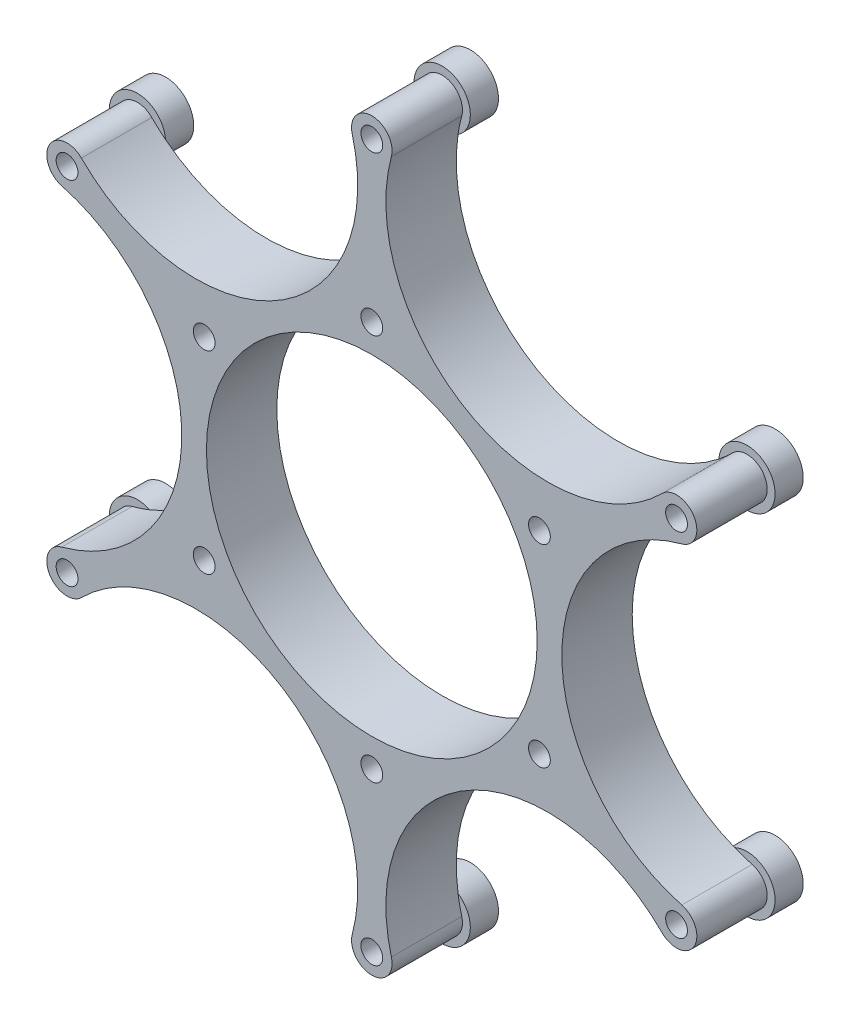
SolidWorks part; units mm, degrees
material "A-玻璃纤维"
ref_plane "前视基准面" through (0, 0, 0) normal (0, 0, 1) x (1, 0, 0)
ref_plane "上视基准面" through (0, 0, 0) normal (0, 1, 0) x (1, 0, 0)
ref_plane "右视基准面" through (0, 0, 0) normal (1, 0, 0) x (0, 0, -1)
sketch "草图1" plane through (0, 0, 0) normal (0, 0, 1) x (1, 0, 0)
  line L0 (0, 0) -> (0, 50) construction
  line L1 (0, 0) -> (43.3013, 25) construction
  line L2 (-43.3013, 25) -> (0, 0) construction
  line L3 (0, 0) -> (-25, 43.3013) construction
  line L4 (-25, 43.3013) -> (-66.3459, 35.9177) construction
  line L5 (-43.3013, 25) -> (-45.7971, 26.441) construction
  line L6 (0, 52.8819) -> (0, 50) construction
  line L7 (0, 0) -> (-2.7837, 49.2541) construction
  line L8 (0, 0) -> (41.2635, 27.0378) construction
  circle A0 centre (0, 0) radius 23.5
  circle A1 centre (0, 0) radius 73 construction
  circle A2 centre (0, 0) radius 50 construction
  circle A3 centre (0, 50) radius 4 construction
  circle A4 centre (43.3013, 25) radius 4 construction
  circle A5 centre (43.3013, -25) radius 4 construction
  circle A6 centre (0, -50) radius 4 construction
  circle A7 centre (-43.3013, -25) radius 4 construction
  circle A8 centre (-43.3013, 25) radius 4 construction
  circle A9 centre (-25, 43.3013) radius 21 construction
  circle A10 centre (-66.3459, 35.9177) radius 21 construction
  arc A13 (0, 52.8819) -> (-2.7837, 49.2541) centre (0, 50) ccw
  arc A14 (-41.2635, 27.0378) -> (-45.7971, 26.441) centre (-43.3013, 25) ccw
  arc A15 (-41.2635, 27.0378) -> (-2.7837, 49.2541) centre (-25, 43.3013) ccw
  arc A16 (2.7837, 49.2541) -> (41.2635, 27.0378) centre (25, 43.3013) ccw
  arc A17 (45.7971, 26.441) -> (41.2635, 27.0378) centre (43.3013, 25) ccw
  arc A18 (2.7837, 49.2541) -> (0, 52.8819) centre (0, 50) ccw
  arc A19 (44.0472, 22.2163) -> (44.0472, -22.2163) centre (50, 0) ccw
  arc A20 (45.7971, -26.441) -> (44.0472, -22.2163) centre (43.3013, -25) ccw
  arc A21 (44.0472, 22.2163) -> (45.7971, 26.441) centre (43.3013, 25) ccw
  arc A22 (41.2635, -27.0378) -> (2.7837, -49.2541) centre (25, -43.3013) ccw
  arc A23 (0, -52.8819) -> (2.7837, -49.2541) centre (0, -50) ccw
  arc A24 (41.2635, -27.0378) -> (45.7971, -26.441) centre (43.3013, -25) ccw
  arc A25 (-2.7837, -49.2541) -> (-41.2635, -27.0378) centre (-25, -43.3013) ccw
  arc A26 (-45.7971, -26.441) -> (-41.2635, -27.0378) centre (-43.3013, -25) ccw
  arc A27 (-2.7837, -49.2541) -> (0, -52.8819) centre (0, -50) ccw
  arc A28 (-44.0472, -22.2163) -> (-44.0472, 22.2163) centre (-50, 0) ccw
  arc A29 (-45.7971, 26.441) -> (-44.0472, 22.2163) centre (-43.3013, 25) ccw
  arc A30 (-44.0472, -22.2163) -> (-45.7971, -26.441) centre (-43.3013, -25) ccw
  circle A31 centre (0, 50) radius 4.8819 construction
  circle A32 centre (-43.3013, 25) radius 4.5 construction
  dimension "D1" = 47
  dimension "D2" = 100
  dimension "D3" = 8
  dimension "D7" = 42
  dimension "D8" = 2
  dimension "D9" = 146
  dimension "D10" = 23
  dimension "D13" = 9
  dimension "D5" = 60
  dimension "D6" = 30
  dimension "D11" = 6
  dimension "D12" = 60
  dimension "D4" = 6
extrude "凸台-拉伸1" add sketch "草图1" along normal mid plane 10 contours A28 A30 A26 A25 A27 A23 A22 A24 A20 A19 A21 A17 A16 A18 A13 A15 A14 A29 A0
sketch "草图2" plane through (0, 0, 5) normal (0, 0, 1) x (1, 0, 0)
  circle A0 centre (0, 50) radius 1.55
  dimension "D1" = 3.1
extrude "切除-拉伸1" cut sketch "草图2" against normal blind 10
pattern_circular "阵列(圆周)1" count 6 over 360 about axis through (0, 0, 0) along (0, 0, 1) of "切除-拉伸1"
sketch "草图3" plane through (0, 0, 5) normal (0, 0, 1) x (1, 0, 0)
  line L0 (0, 0) -> (0, 27.5) construction
  line L1 (0, 0) -> (23.8157, 13.75) construction
  circle A1 centre (0, 27.5) radius 1.55
  circle A2 centre (0, 0) radius 27.5
  circle A3 centre (0, 0) radius 27.5 construction
  circle A4 centre (23.8157, 13.75) radius 1.55
  circle A5 centre (23.8157, -13.75) radius 1.55
  circle A6 centre (0, -27.5) radius 1.55
  circle A7 centre (-23.8157, -13.75) radius 1.55
  circle A8 centre (-23.8157, 13.75) radius 1.55
  dimension "D2" = 3.1
  dimension "D4" = 60
  dimension "D1" = 4
  dimension "D3" = 6
extrude "切除-拉伸2" cut sketch "草图3" against normal blind 10
sketch "草图4" plane through (0, 0, -5) normal (0, 0, -1) x (-1, 0, 0)
  circle A0 centre (-43.3013, 25) radius 1.5
  circle A1 centre (-43.3013, 25) radius 4
  dimension "D1" = 3
  dimension "D2" = 8
extrude "凸台-拉伸2" add sketch "草图4" along normal blind 4
pattern_circular "阵列(圆周)2" count 6 over 360 about axis through (0, 0, 0) along (0, 0, 1) of "凸台-拉伸2"
